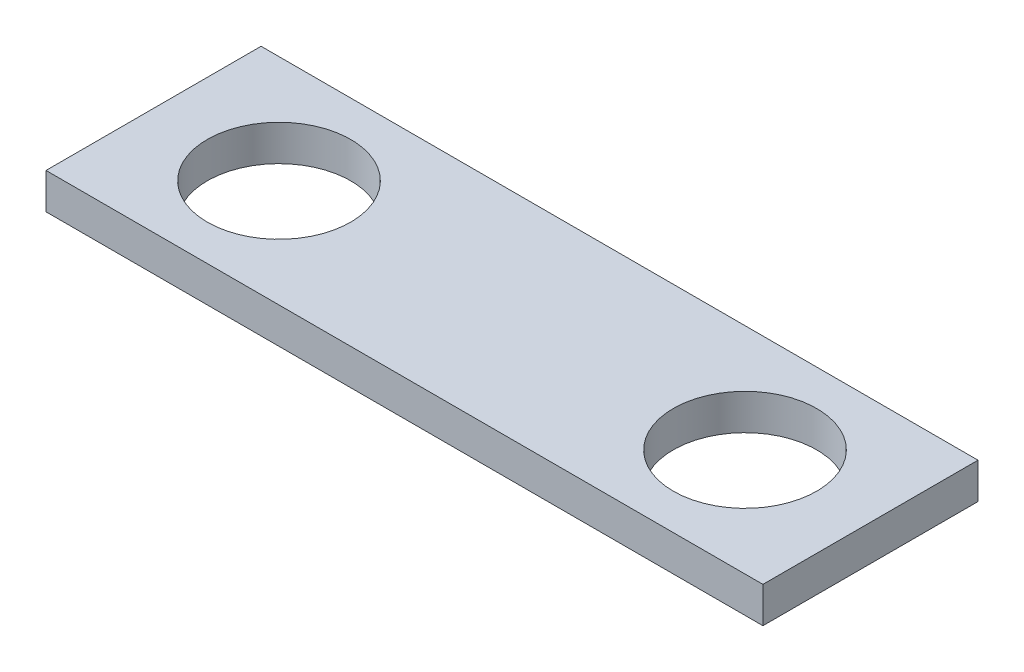
SolidWorks part; units mm, degrees
ref_plane "Front Plane" through (0, 0, 0) normal (0, 0, 1) x (1, 0, 0)
ref_plane "Top Plane" through (0, 0, 0) normal (0, 1, 0) x (1, 0, 0)
ref_plane "Right Plane" through (0, 0, 0) normal (1, 0, 0) x (0, 0, -1)
sketch "Sketch1" plane through (0, 0, 0) normal (0, 1, 0) x (1, 0, 0)
  line L1 (0, 0) -> (40, 0)
  line L2 (0, 0) -> (0, 12)
  line L3 (0, 12) -> (40, 12)
  line L4 (40, 0) -> (40, 12)
  dimension "D1" = 40
  dimension "D2" = 12
extrude "Boss-Extrude1" add sketch "Sketch1" along normal blind 2
sketch "Sketch2" plane through (0, 2, 0) normal (0, 1, 0) x (1, 0, 0)
  line L0 (0, 12) -> (0, 0) construction
  line L1 (0, 0) -> (40, 0) construction
  line L2 (20, 12) -> (20, 0)
  line L3 (40, 12) -> (0, 12) construction
  circle A0 centre (7, 6) radius 4
  circle A1 centre (33, 6) radius 4
  dimension "D1" = 8
  dimension "D2" = 7
  dimension "D3" = 6
extrude "Cut-Extrude3" cut sketch "Sketch2" against normal through all contours A0 | A1
